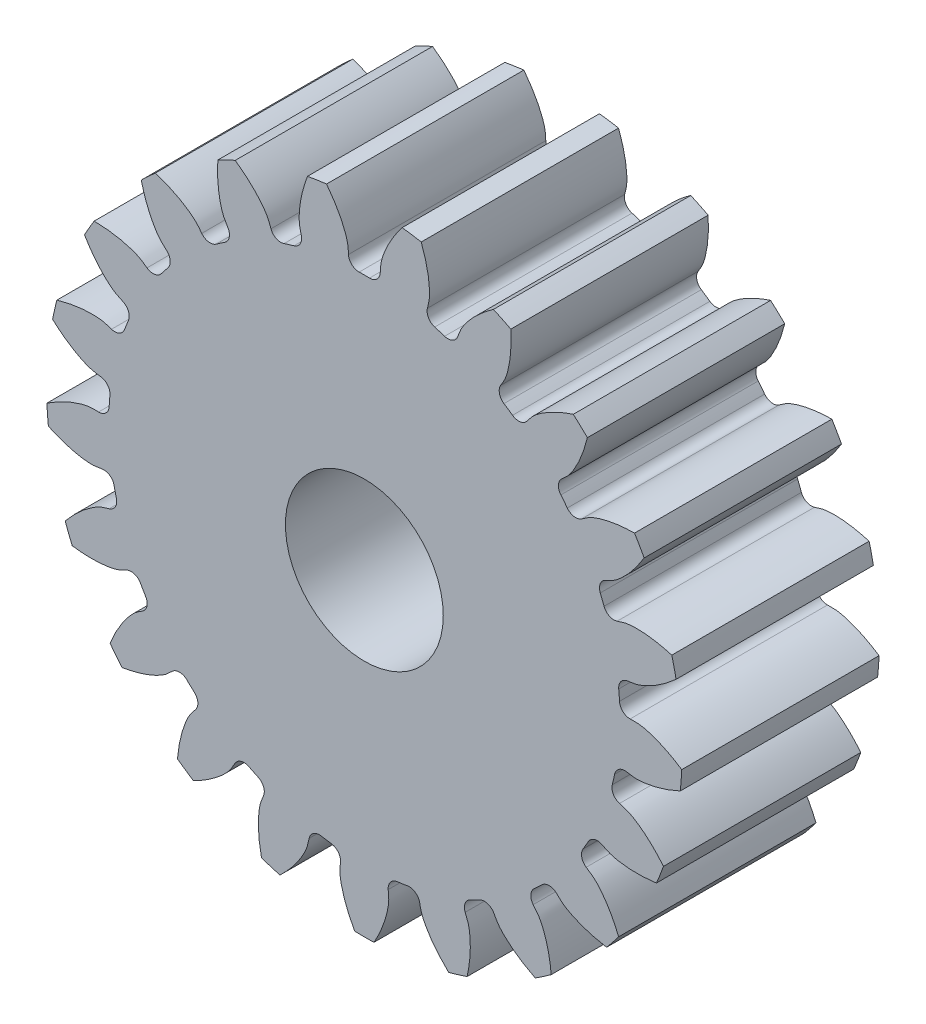
SolidWorks part; units mm, degrees
ref_plane "前视基准面" through (0, 0, 0) normal (0, 0, 1) x (1, 0, 0)
ref_plane "上视基准面" through (0, 0, 0) normal (0, 1, 0) x (1, 0, 0)
ref_plane "右视基准面" through (0, 0, 0) normal (1, 0, 0) x (0, 0, -1)
other "Configuration Table"
ref_axis "Axis1" through (0, 0, -88.99) along (0, 0, 1)
sketch "草图1" plane through (0, 0, 0) normal (0, 0, 1) x (1, 0, 0)
  circle A0 centre (0, 0) radius 8.05
extrude "LaShenA" add sketch "草图1" along normal blind 5
sketch "SketchA" plane through (0, 0, 5) normal (0, 0, 1) x (1, 0, 0)
  line L0 (0, 0) -> (0, 8.05) construction
  arc A0 (0.1314, 6.4737) -> (-0.1314, 6.4737) centre (0, 0) ccw
  arc A1 (1.2602, 8.3441) -> (-1.2602, 8.3441) centre (0, 0) ccw
  arc A2 (-0.1314, 6.4737) -> (-0.4023, 6.7236) centre (-0.1368, 6.7396) cw
  arc A3 (0.4023, 6.7236) -> (0.1314, 6.4737) centre (0.1368, 6.7396) cw
  circle A4 centre (0, 0) radius 6.9067 construction
  circle A5 centre (0, 0) radius 8.05 construction
  circle A6 centre (0, 0) radius 6.475 construction
  circle A7 centre (0, 0) radius 7.35 construction
  spline S0 degree 3 poles (0.4023, 6.7236) (0.4057, 6.7809) (0.4081, 6.8586) (0.4207, 6.9451) (0.4293, 6.9853) (0.437, 7.0171) (0.4468, 7.0536) (0.459, 7.0946) (0.474, 7.14) (0.4918, 7.1898) (0.5128, 7.2438) (0.5372, 7.3018) (0.5652, 7.3637) (0.5971, 7.4294) (0.6331, 7.4987) (0.6733, 7.5714) (0.7181, 7.6473) (0.7676, 7.7262) (0.8219, 7.808) (0.8814, 7.8923) (0.9461, 7.9791) (1.0163, 8.0681) (1.1194, 8.1919) (1.2023, 8.2833) (1.2602, 8.3441) knots 0.123319 0.123319 0.123319 0.123319 0.203409 0.232856 0.245818 0.261137 0.278814 0.298847 0.321236 0.345983 0.373086 0.402547 0.434364 0.468537 0.505068 0.543956 0.5852 0.628801 0.674759 0.723074 0.773745 0.826774 0.882159 1 1 1 1
  spline S1 degree 3 poles (-0.4023, 6.7236) (-0.4057, 6.7809) (-0.4081, 6.8586) (-0.4207, 6.9451) (-0.4293, 6.9853) (-0.437, 7.0171) (-0.4468, 7.0536) (-0.459, 7.0946) (-0.474, 7.14) (-0.4918, 7.1898) (-0.5128, 7.2438) (-0.5372, 7.3018) (-0.5652, 7.3637) (-0.5971, 7.4294) (-0.6331, 7.4987) (-0.6733, 7.5714) (-0.7181, 7.6473) (-0.7676, 7.7262) (-0.8219, 7.808) (-0.8814, 7.8923) (-0.9461, 7.9791) (-1.0163, 8.0681) (-1.1194, 8.1919) (-1.2023, 8.2833) (-1.2602, 8.3441) knots 0.123319 0.123319 0.123319 0.123319 0.203409 0.232856 0.245818 0.261137 0.278814 0.298847 0.321236 0.345983 0.373086 0.402547 0.434364 0.468537 0.505068 0.543956 0.5852 0.628801 0.674759 0.723074 0.773745 0.826774 0.882159 1 1 1 1
  dimension "D1" = 0.266
  dimension "Db" = 13.8135
  dimension "Da" = 16.1
  dimension "Df" = 12.95
  dimension "Dn" = 14.7
extrude "Cut-ExtrudeA" cut sketch "SketchA" against normal blind 5
pattern_circular "www.KYTool.cn" count 21 over 360 about axis through (0, 0, -88.99) along (0, 0, 1) of "Cut-ExtrudeA"
sketch "草图3" plane through (0, 0, 5) normal (0, 0, 1) x (1, 0, 0)
  circle A0 centre (0, 0) radius 2
  dimension "D1" = 4
extrude "切除-拉伸2" cut sketch "草图3" against normal through all
